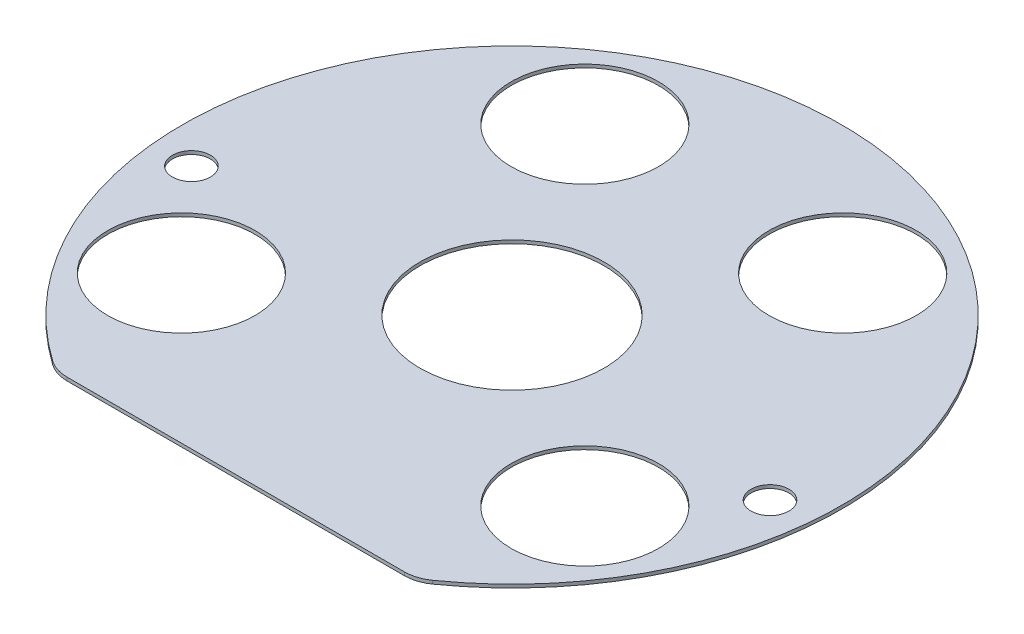
SolidWorks part; units mm, degrees
material "6063-T6"
ref_plane "Front Plane" through (0, 0, 0) normal (0, 0, 1) x (1, 0, 0)
ref_plane "Top Plane" through (0, 0, 0) normal (0, 1, 0) x (1, 0, 0)
ref_plane "Right Plane" through (0, 0, 0) normal (1, 0, 0) x (0, 0, -1)
sketch "Sketch1" plane through (0, 0, 0) normal (0, 1, 0) x (1, 0, 0)
  line L0 (0, 89.5) -> (0, -75) construction
  line L2 (-89.5, 0) -> (89.5, 0) construction
  line L3 (-48.839, -75) -> (48.839, -75)
  arc A0 (48.839, -75) -> (-48.839, -75) centre (0, 0) ccw
  dimension "D1" = 179
  dimension "D2" = 75
extrude "Boss-Extrude1" add sketch "Sketch1" against normal blind 0.91
sketch "Sketch9" plane through (0, 0, 0) normal (0, 1, 0) x (1, 0, 0)
  line L0 (0, 89.5) -> (0, -75) construction
  line L1 (48.839, -75) -> (-48.839, -75) construction
  line L2 (78.5412, -8.5017) -> (-78.5412, -8.5017) construction
  arc A12 (48.839, -75) -> (-48.839, -75) centre (0, 0) ccw construction
  circle A13 centre (78.5412, -8.5017) radius 5.15
  circle A15 centre (-78.5412, -8.5017) radius 5.15
  point P8 (0, -8.5017)
  dimension "D3" = 10.3
  dimension "D4" = 10.3
  dimension "D2" = 66.4983
  dimension "D1" = 157.0824
extrude "Cut-Extrude3" cut sketch "Sketch9" against normal through all
sketch "Vision Pattern" plane through (0, 0, 0) normal (0, 1, 0) x (1, 0, 0)
  line L0 (64.8074, -55) -> (-64.8074, -55) construction
  line L1 (0, 0) -> (0, -55) construction
  circle A0 centre (0, 0) radius 85 construction
  circle A1 centre (0, 0) radius 25
  circle A2 centre (54.7723, -35) radius 20
  circle A3 centre (-54.7723, -35) radius 20
  circle A4 centre (35, 54.7723) radius 20
  circle A5 centre (-35, 54.7723) radius 20
  circle A6 centre (0, 0) radius 65 construction
  dimension "D1" = 170
  dimension "D3" = 50
  dimension "D4" = 40
  dimension "D2" = 55
  dimension "D5" = 35
  dimension "D8" = 65
  dimension "D6" = 35
  dimension "D7" = 35
extrude "Cut-Extrude4" cut sketch "Vision Pattern" against normal through all
fillet "Fillet1" radius 10 2 edges at (-48.839, -0.455, 75) (48.839, -0.455, 75)
equation "\"D4@Sketch9\"=\"D3@Sketch9\""
equation "\"D1@Vision Pattern\" = 85 * 2"
equation "\"D7@Vision Pattern\"=\"D6@Vision Pattern\""
equation "\"20Gauge\"= .911"
